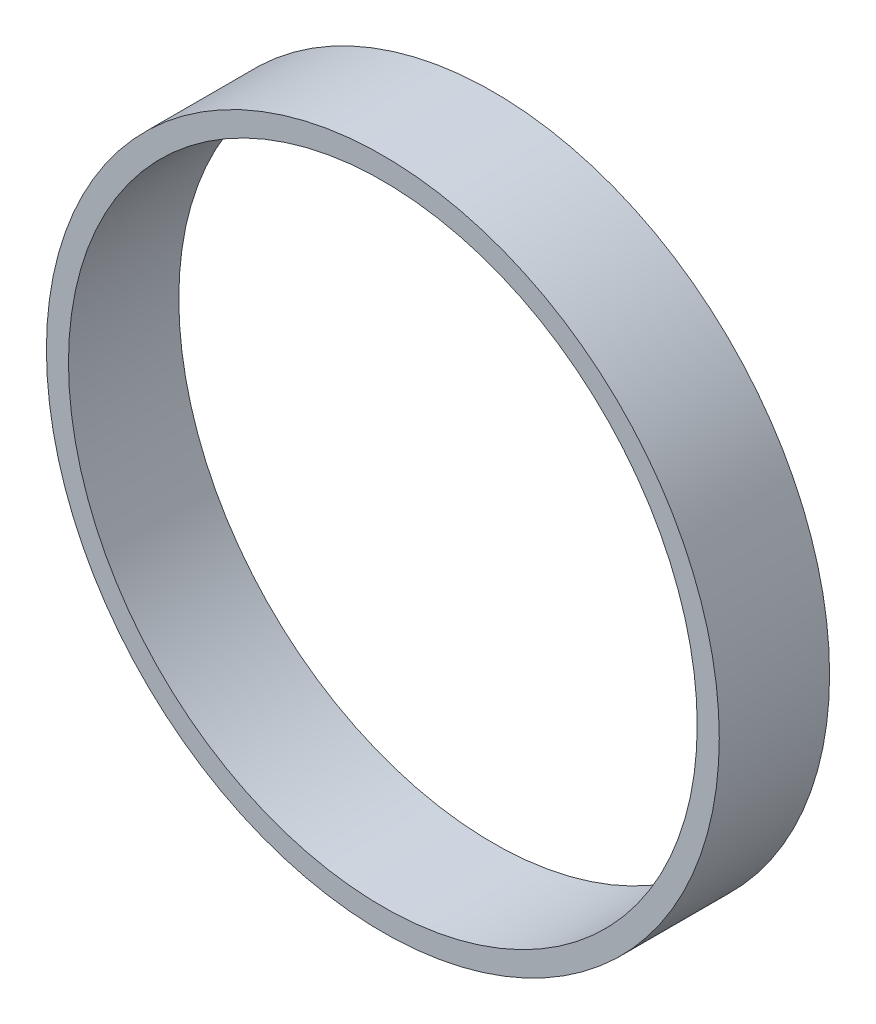
SolidWorks part; units mm, degrees
ref_plane "Plano frontal" through (0, 0, 0) normal (0, 0, 1) x (1, 0, 0)
ref_plane "Plano superior" through (0, 0, 0) normal (0, 1, 0) x (1, 0, 0)
ref_plane "Plano direito" through (0, 0, 0) normal (1, 0, 0) x (0, 0, -1)
sketch "Esboço1" plane through (0, 0, 0) normal (0, 0, 1) x (1, 0, 0)
  circle A0 centre (0, 0) radius 30.5
  circle A1 centre (0, 0) radius 28.5
  dimension "D1" = 57
  dimension "D2" = 61
extrude "Ressalto-extrusão1" add sketch "Esboço1" along normal blind 10
